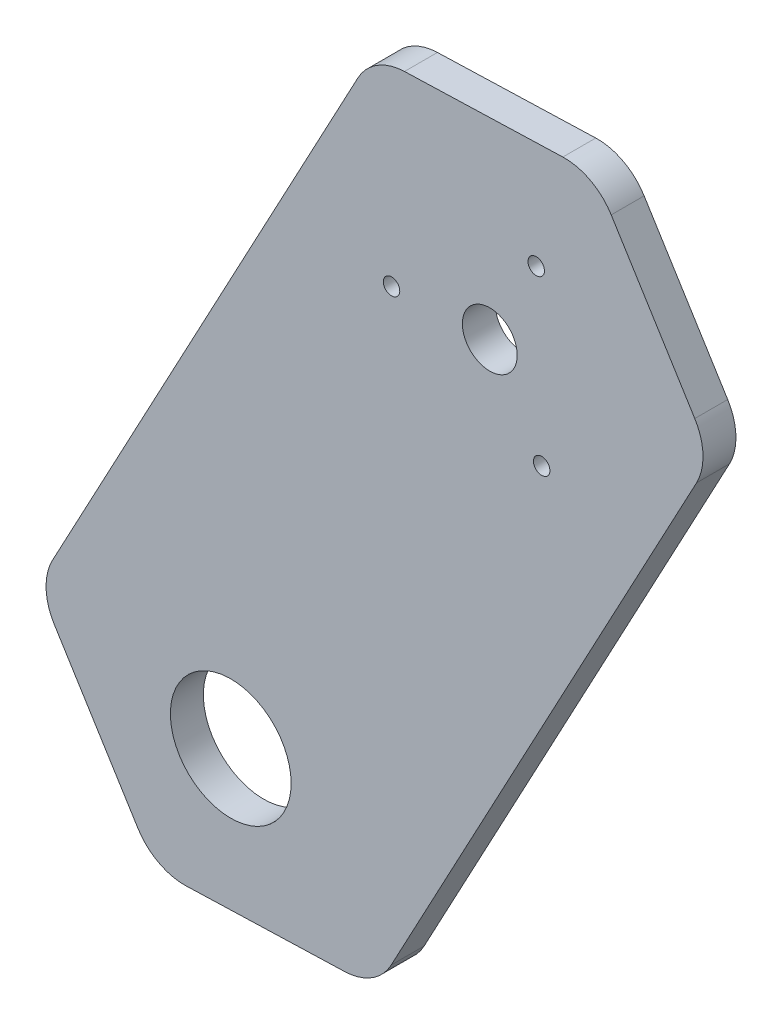
SolidWorks part; units mm, degrees
ref_plane "Front Plane" through (0, 0, 0) normal (0, 0, 1) x (1, 0, 0)
ref_plane "Top Plane" through (0, 0, 0) normal (0, 1, 0) x (1, 0, 0)
ref_plane "Right Plane" through (0, 0, 0) normal (1, 0, 0) x (0, 0, -1)
sketch "Sketch1" plane through (0, 0, 0) normal (0, 0, 1) x (1, 0, 0)
  line L6 (32.7617, 392.6912) -> (61.6144, 393.6149)
  line L7 (70.4302, 388.8946) -> (85.6566, 364.3693)
  line L8 (85.9766, 354.3744) -> (30.3393, 250.4646)
  line L9 (21.8435, 245.19) -> (-7.0092, 244.2663)
  line L10 (-15.825, 248.9866) -> (-31.0514, 273.5119)
  line L11 (-31.3714, 283.5068) -> (24.2659, 387.4166)
  circle A11 centre (1.1048, 270.0128) radius 11
  circle A12 centre (57.7585, 342.9489) radius 1.5
  circle A13 centre (56.7655, 373.9664) radius 1.5
  circle A14 centre (30.4001, 357.5976) radius 1.5
  circle A15 centre (48.308, 358.171) radius 5
  arc A16 (32.7617, 392.6912) -> (24.2659, 387.4166) centre (33.0817, 382.6963) ccw
  arc A17 (70.4302, 388.8946) -> (61.6144, 393.6149) centre (61.9344, 383.62) ccw
  arc A18 (85.9766, 354.3744) -> (85.6566, 364.3693) centre (77.1608, 359.0947) ccw
  arc A19 (21.8435, 245.19) -> (30.3393, 250.4646) centre (21.5235, 255.1849) ccw
  arc A20 (-15.825, 248.9866) -> (-7.0092, 244.2663) centre (-7.3292, 254.2612) ccw
  arc A21 (-31.3714, 283.5068) -> (-31.0514, 273.5119) centre (-22.5555, 278.7865) ccw
  point P5 (50.953, 393.2736)
  dimension "D2" = 10
  dimension "D9" = 3
  dimension "D10" = 22
  dimension "D20" = 10
  dimension "D21" = 19.4833
  dimension "D22" = 19.4833
  dimension "D24" = 19.4833
  dimension "D1" = 117.8675
  dimension "D3" = 60
  dimension "D4" = 60
  dimension "D5" = 60
  dimension "D6" = 60
  dimension "D7" = 60
  dimension "D8" = 60
  dimension "D11" = 28.8675
  dimension "D12" = 28.8675
  dimension "D13" = 245.19
  dimension "D14" = 21.8435
  dimension "D15" = 244.3655
  dimension "D16" = 25.4737
  dimension "D17" = 25.4737
  dimension "D18" = 100
  dimension "D19" = 35
  dimension "D23" = 19.4833
  dimension "D25" = 31.0333
  dimension "D26" = 31.0333
extrude "Boss-Extrude1" add sketch "Sketch1" along normal blind 6 separate body
